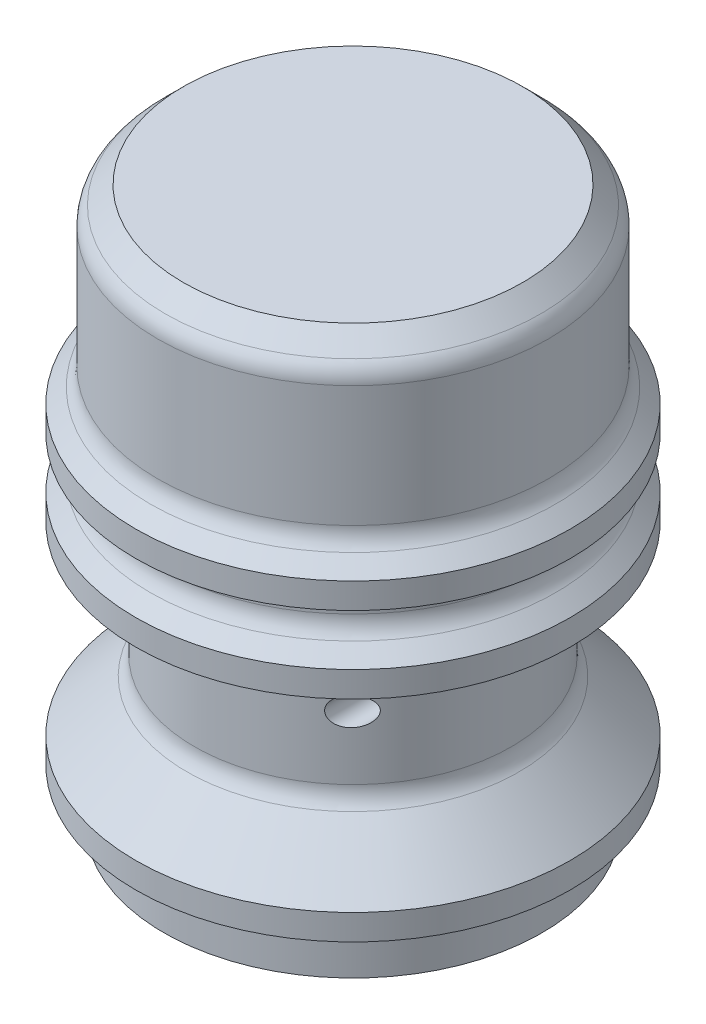
SolidWorks part; units mm, degrees
ref_plane "Plano frontal" through (0, 0, 0) normal (0, 0, 1) x (1, 0, 0)
ref_plane "Plano superior" through (0, 0, 0) normal (0, 1, 0) x (1, 0, 0)
ref_plane "Plano direito" through (0, 0, 0) normal (1, 0, 0) x (0, 0, -1)
sketch "Cut_1" plane through (0, 0, 0) normal (0, 1, 0) x (1, 0, 0)
  line L0 (4.658, 6.0576) -> (4.658, 2.8486) construction
  line L1 (3.856, 3.8656) -> (3.856, 6.5972)
  line L2 (5.46, 0) -> (5.46, 5.346)
  line L3 (3.856, 3.8656) -> (4.658, 3.8656) construction
  line L4 (4.658, 3.8656) -> (5.46, 3.8656) construction
  circle A0 centre (0, 0) radius 5.46
  circle A2 centre (0, 0) radius 7.6414
  circle A4 centre (0, 0) radius 3.105
  dimension "D1" = 10.92
  dimension "D5" = 15.2829
  dimension "D6" = 6.21
  dimension "D2" = 4.658
  dimension "D3" = 1.604
  dimension "D4" = 3.209
  dimension "D7" = 0.802
sketch "Cut_2" plane through (0, 0, 0) normal (0, 1, 0) x (1, 0, 0)
  line L0 (4.889, 0) -> (4.889, 3.8203)
  line L1 (3.797, 3.0798) -> (3.797, 4.9071)
  line L2 (3.797, 3.0798) -> (4.343, 3.0798) construction
  line L3 (4.343, 3.0798) -> (4.889, 3.0798) construction
  line L4 (4.343, 4.4311) -> (4.343, 2.2451) construction
  circle A0 centre (0, 0) radius 4.889
  circle A1 centre (0, 0) radius 6.2046
  circle A2 centre (0, 0) radius 4.889
  circle A3 centre (0, 0) radius 5.798
  dimension "D1" = 9.778
  dimension "D2" = 4.343
  dimension "D5" = 12.4091
  dimension "D6" = 9.778
  dimension "D7" = 11.596
  dimension "D3" = 1.092
  dimension "D4" = 2.186
  dimension "D8" = 0.546
sketch "Esboço4" plane through (0, 0, 0) normal (0, 0, 1) x (1, 0, 0)
  line L0 (0, 0) -> (0, 9.8449) construction
  line L1 (4.889, 0) -> (4.889, 4.889) construction
  line L2 (3.105, 1) -> (3.105, 10.329)
  line L3 (3.105, 10.329) -> (5.46, 12.684)
  line L4 (5.46, 12.684) -> (5.46, 19.658)
  line L5 (5.46, 19.658) -> (0, 19.658)
  line L6 (0, 19.658) -> (0, 21.658)
  line L7 (0, 21.658) -> (7.6414, 21.658)
  line L8 (7.6414, 21.658) -> (7.6414, 10.732)
  line L9 (7.6414, 10.732) -> (6.2046, 10.732)
  line L10 (6.2046, 10.732) -> (6.2046, 4)
  line L11 (6.2046, 4) -> (7.4, 4)
  line L12 (7.4, 4) -> (7.4, 0)
  line L13 (7.4, 0) -> (5.798, 0)
  line L14 (4.889, 4.4734) -> (4.889, 4.889)
  line L16 (4.889, 4.889) -> (4.889, 9.232)
  line L17 (4.889, 9.232) -> (4.105, 9.232)
  line L18 (4.105, 9.232) -> (4.105, 1)
  line L19 (4.105, 1) -> (3.105, 1)
  line L21 (6.2046, 4) -> (6.2046, 0) construction
  line L22 (5.798, 0) -> (5.798, 2.899)
  line L23 (4.889, 0) -> (-4.889, 0) construction
  line L24 (5.798, 2.899) -> (4.889, 4.4734)
  line L25 (5.46, 12.684) -> (5.46, 0) construction
  line L26 (3.105, 1) -> (3.105, 0) construction
  line L28 (7.6414, 10.732) -> (7.6414, 0) construction
  line L29 (4.889, 4.4734) -> (4.889, 0) construction
  line L32 (0, 9.232) -> (4.28, 9.232) construction
  dimension "D1" = 1
  dimension "D2" = 14.8
  dimension "D3" = 1
  dimension "D4" = 4
  dimension "D5" = 45
  dimension "D6" = 9.329
  dimension "D7" = 4.343
  dimension "D8" = 2
  dimension "D9" = 30
  dimension "D10" = 9.329
  dimension "D11" = 1.5
  dimension "D12" = 4.889
  dimension "D13" = 1.1954
  dimension "D14" = 4.28
  dimension "D16" = 2.899
revolve "Revolução1" add sketch "Esboço4" angle 360 about L0
sketch "Esboço5" plane through (0, 0, 0) normal (0, 0, 1) x (1, 0, 0)
  line L0 (0, 0) -> (0, 18.356) construction
  line L1 (4.889, 0) -> (-4.889, 0) construction
  line L2 (0, 18.356) -> (0, 19.658) construction
  line L3 (0, 18.356) -> (4.658, 18.356) construction
  line L4 (4.658, 18.356) -> (4.658, 0) construction
  line L5 (-5.46, 19.658) -> (5.46, 19.658) construction
  line L6 (-4.105, 0) -> (-4.105, 8.186) construction
  line L7 (5.46, 0) -> (-5.46, 0) construction
  line L8 (-4.105, 8.186) -> (-4.105, 9.232) construction
  line L9 (-4.105, 8.186) -> (-4.343, 8.186) construction
  line L10 (-4.343, 8.186) -> (-4.343, 0) construction
  line L15 (-4.343, 0) -> (0, 0) construction
  line L16 (0, 0) -> (4.343, 0) construction
  line L17 (4.889, 0) -> (-4.889, 0) construction
  circle A0 centre (4.658, 18.356) radius 0.802
  circle A1 centre (-4.343, 8.186) radius 0.546
  dimension "D1" = 1.604
  dimension "D3" = 1.092
  dimension "D2" = 1.302
  dimension "D4" = 1.046
extrude "Inlet_1" [suppressed] cut sketch "Esboço5" against normal through all contours A0
pattern_circular "PadrãoCircular1" [suppressed] count 4 over 360
ref_plane "Plano1" through (0, 0, -10) normal (0, 0, 1) x (1, 0, 0)
sketch "Esboço9" plane through (0, 0, -10) normal (0, 0, 1) x (1, 0, 0)
  circle A0 centre (-4.343, 8.186) radius 0.546
  circle A1 centre (-4.343, 8.186) radius 0.546 construction
extrude "Corte-extrusão1" cut sketch "Esboço9" along normal up to surface (6.9202 mm away) contours A0
pattern_circular "PadrãoCircular2" count 4 over 360 of "Corte-extrusão1"
chamfer "Chanfro1" distance 1 angle 45 1 edges at (0, 21.658, -7.6414)
fillet "Filete3" radius 1 1 edges at (0, 20.658, 7.6414)
fillet "Filete_topo" radius 0.35 3 edges at (0, 9.232, -4.105) (0, 9.232, -4.889) (0, 19.658, -5.46)
fillet "Filete_base" radius 2 4 edges at (0, 10.329, -3.105) (0, 12.684, -5.46) (0, 4.4734, -4.889) (0, 2.899, -5.798)
sketch "Esboço11" plane through (0, 0, 0) normal (0, 0, 1) x (1, 0, 0)
  line L0 (6.2046, 10.232) -> (8.5, 10.232)
  line L1 (8.5, 10.232) -> (8.5, 11.232)
  line L2 (8.5, 11.232) -> (7.6414, 12.0906)
  line L3 (7.6414, 12.0906) -> (7.6414, 13.232)
  line L4 (7.6414, 13.232) -> (8.5, 13.232)
  line L5 (8.5, 13.232) -> (8.5, 14.232)
  line L6 (8.5, 14.232) -> (7.6414, 15.0906)
  line L7 (7.6414, 15.0906) -> (7.1414, 15.0906)
  line L8 (7.1414, 15.0906) -> (7.1414, 11.232)
  line L9 (7.1414, 11.232) -> (5.7046, 11.232)
  line L10 (5.7046, 11.232) -> (5.7046, 10.232)
  line L11 (5.7046, 10.232) -> (6.2046, 10.232)
  line L12 (7.4, 2) -> (8.5, 2)
  line L13 (8.5, 2) -> (8.5, 3)
  line L14 (8.5, 3) -> (6.2046, 5.2954)
  line L15 (6.2046, 5.2954) -> (5.7046, 5.2954)
  line L16 (5.7046, 5.2954) -> (5.7046, 4)
  line L17 (5.7046, 4) -> (6.9, 2)
  line L18 (6.9, 2) -> (7.4, 2)
  line L19 (7.6414, 15.0906) -> (7.6414, 10.732) construction
  line L20 (5.7046, 4) -> (6.2046, 4) construction
  line L22 (6.2046, 10.232) -> (6.2046, 10.732) construction
  line L23 (6.2046, 10.732) -> (6.2046, 11.232) construction
  line L26 (0, 0) -> (0, 7.0334) construction
  line L27 (7.4, 2) -> (7.4, 0) construction
  line L30 (6.2046, 5.2954) -> (6.2046, 4) construction
  dimension "D1" = 0.5
  dimension "D2" = 0.5
  dimension "D3" = 1
  dimension "D4" = 4
  dimension "D5" = 45
  dimension "D6" = 0.5
  dimension "D7" = 0.5
  dimension "D8" = 17
  dimension "D9" = 0.5
  dimension "D10" = 2
  dimension "D11" = 0.5
  dimension "D12" = 45
  dimension "D13" = 1
  dimension "D15" = 0.8586
  dimension "D16" = 1.1414
revolve "Revolução2" add sketch "Esboço11" angle 360 about L26
fillet "Filete4" radius 1 4 edges at (0, 12.0906, -7.6414) (0, 15.0906, 7.6414) (0, 5.2954, 6.2046) (0, 10.232, -6.2046)
fillet "Filete5" radius 0.5 2 edges at (0, 2, -7.4) (0, 13.232, -7.6414)
sketch "Esboço12" plane through (0, 0, 0) normal (0, 0, 1) x (1, 0, 0)
  line L0 (-3.7559, 1) -> (-3.7559, 10.0858)
  line L1 (-3.7559, 10.0858) -> (-6.6937, 13.5436)
  line L2 (-6.6937, 13.5436) -> (-6.6937, 20.4631)
  line L3 (-6.6937, 20.4631) -> (0, 20.4631)
  line L4 (0, 20.4631) -> (0, 1)
  line L5 (0, 1) -> (-3.7559, 1)
  line L6 (0, 0) -> (0, -2.4571) construction
  line L7 (-4.105, 1) -> (4.105, 1) construction
  point P8 (-3.292, 1.0102)
  point P10 (-3.7559, 0.8442)
  dimension "D1" = 6.6937
  dimension "D2" = 40.351
  dimension "D3" = 7.5118
  dimension "D4" = 9.0858
  dimension "D5" = 6.9195
revolve "Revolução3" add sketch "Esboço12" angle 360 about L6
equation "\"D2@Esboço5\"=\"D1@Esboço5\"/2+0.5"
equation "\"D4@Esboço5\"=\"D3@Esboço5\"/2+0.5"
